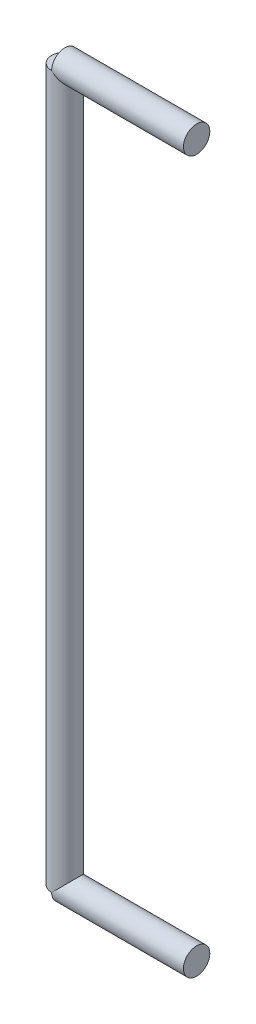
SolidWorks part; units mm, degrees
ref_plane "Front Plane" through (0, 0, 0) normal (0, 0, 1) x (1, 0, 0)
ref_plane "Top Plane" through (0, 0, 0) normal (0, 1, 0) x (1, 0, 0)
ref_plane "Right Plane" through (0, 0, 0) normal (1, 0, 0) x (0, 0, -1)
sketch "Sketch1" plane through (0, 0, 0) normal (0, 1, 0) x (1, 0, 0)
  circle A0 centre (0, 0) radius 0.5
  dimension "D1" = 1
extrude "Boss-Extrude2" add sketch "Sketch1" along normal blind 27
sketch "Sketch9" plane through (0, 0, 0) normal (1, 0, 0) x (0, 0, -1)
  line L0 (0.5, 27) -> (-0.5, 27) construction
  line L1 (-0.5, 0) -> (0.5, 0) construction
  circle A0 centre (0, 0) radius 0.5
  circle A1 centre (0, 27) radius 0.5
  point P4 (0, 0)
  point P7 (0, 0)
  point P8 (0, 0)
  dimension "D1" = 1
  dimension "D2" = 1
extrude "Boss-Extrude3" add sketch "Sketch9" along normal blind 5
